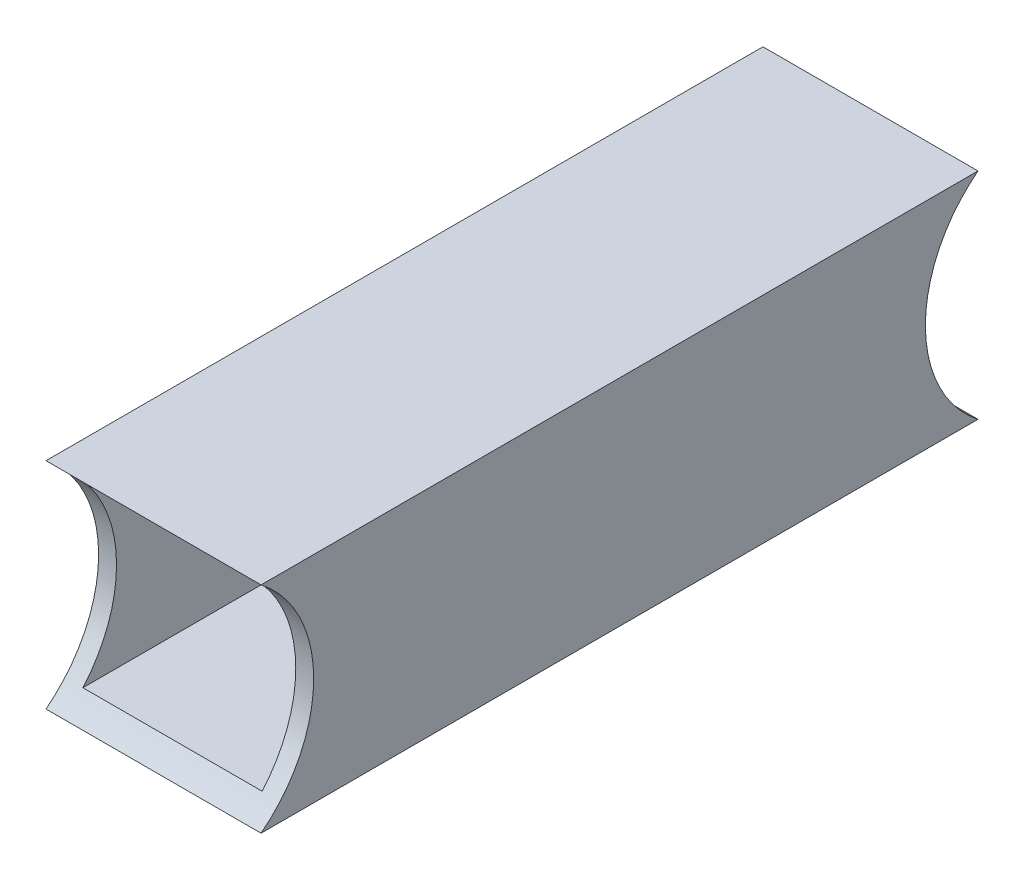
SolidWorks part; units mm, degrees
material "6063-T5"
ref_plane "Front Plane" through (0, 0, 0) normal (0, 0, 1) x (1, 0, 0)
ref_plane "Top Plane" through (0, 0, 0) normal (0, 1, 0) x (1, 0, 0)
ref_plane "Right Plane" through (0, 0, 0) normal (1, 0, 0) x (0, 0, -1)
sketch "Sketch1" plane through (0, 0, 0) normal (1, 0, 0) x (0, 0, -1)
  line L1 (0, 0) -> (156.624, 0)
  line L2 (0, 0) -> (0, 38.1)
  line L3 (0, 38.1) -> (156.624, 38.1)
  line L4 (156.624, 0) -> (156.624, 38.1)
  circle A0 centre (0, 19.05) radius 24.13
  circle A1 centre (156.624, 19.05) radius 24.13
  dimension "D3" = 48.26
  dimension "D4" = 48.26
  dimension "D1" = 156.624
  dimension "D2" = 38.1
extrude "Boss-Extrude1" add sketch "Sketch1" along normal blind 38.1 contours A1 L3 A0 L1
sketch "Sketch2" plane through (0, 0, 0) normal (0, 0, 1) x (1, 0, 0)
  line L0 (3.175, 34.925) -> (3.175, 3.175)
  line L1 (3.175, 3.175) -> (34.925, 3.175)
  line L2 (34.925, 3.175) -> (34.925, 34.925)
  line L3 (34.925, 34.925) -> (3.175, 34.925)
  line L4 (0, 38.1) -> (0, 0)
  line L5 (0, 0) -> (38.1, 0)
  line L6 (38.1, 0) -> (38.1, 38.1)
  line L7 (38.1, 38.1) -> (0, 38.1)
  line L8 (0, 38.1) -> (0, 0) construction
  line L9 (0, 0) -> (38.1, 0) construction
  line L10 (38.1, 0) -> (38.1, 38.1) construction
  line L11 (38.1, 38.1) -> (0, 38.1) construction
  dimension "D1" = 0
  dimension "D2" = 3.175
extrude "Cut-Extrude1" cut sketch "Sketch2" against normal through all
